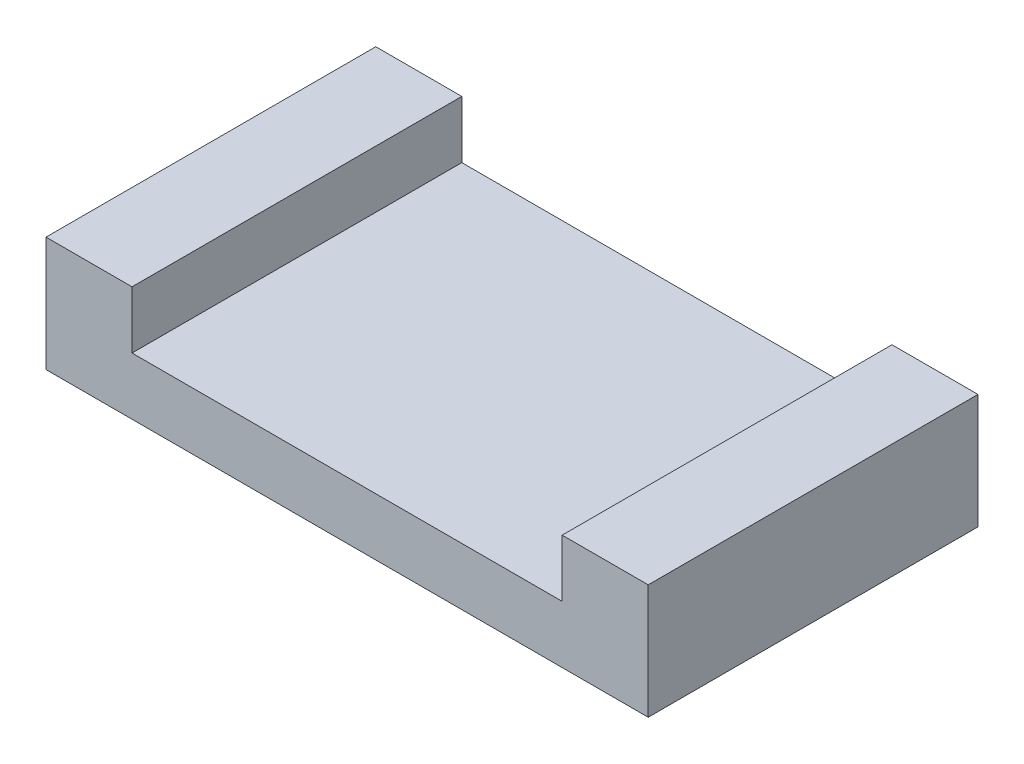
SolidWorks part; units mm, degrees
ref_plane "Front Plane" through (0, 0, 0) normal (0, 0, 1) x (1, 0, 0)
ref_plane "Top Plane" through (0, 0, 0) normal (0, 1, 0) x (1, 0, 0)
ref_plane "Right Plane" through (0, 0, 0) normal (1, 0, 0) x (0, 0, -1)
sketch "Sketch1" plane through (0, 0, 0) normal (0, 1, 0) x (1, 0, 0)
  line L1 (105, -57.5) -> (-105, -57.5)
  line L2 (105, -57.5) -> (105, 57.5)
  line L3 (105, 57.5) -> (-105, 57.5)
  line L4 (-105, -57.5) -> (-105, 57.5)
  line L5 (105, -57.5) -> (-105, 57.5) construction
  line L6 (105, 57.5) -> (-105, -57.5) construction
  point P0 (0, 0)
  dimension "D1" = 210
  dimension "D4" = 115
extrude "Boss-Extrude1" add sketch "Sketch1" along normal blind 20
sketch "Sketch3" plane through (0, 20, 0) normal (0, 1, 0) x (1, 0, 0)
  line L0 (-105, -57.5) -> (105, -57.5) construction
  line L1 (-105, 57.5) -> (-75, 57.5)
  line L2 (-105, 57.5) -> (-105, -57.5)
  line L3 (-105, -57.5) -> (-75, -57.5)
  line L4 (-75, 57.5) -> (-75, -57.5)
  line L6 (105, 57.5) -> (75, 57.5)
  line L7 (105, 57.5) -> (105, -57.5)
  line L8 (105, -57.5) -> (75, -57.5)
  line L9 (75, 57.5) -> (75, -57.5)
  dimension "D1" = 30
  dimension "D2" = 30
extrude "Boss-Extrude2" add sketch "Sketch3" along normal blind 20
